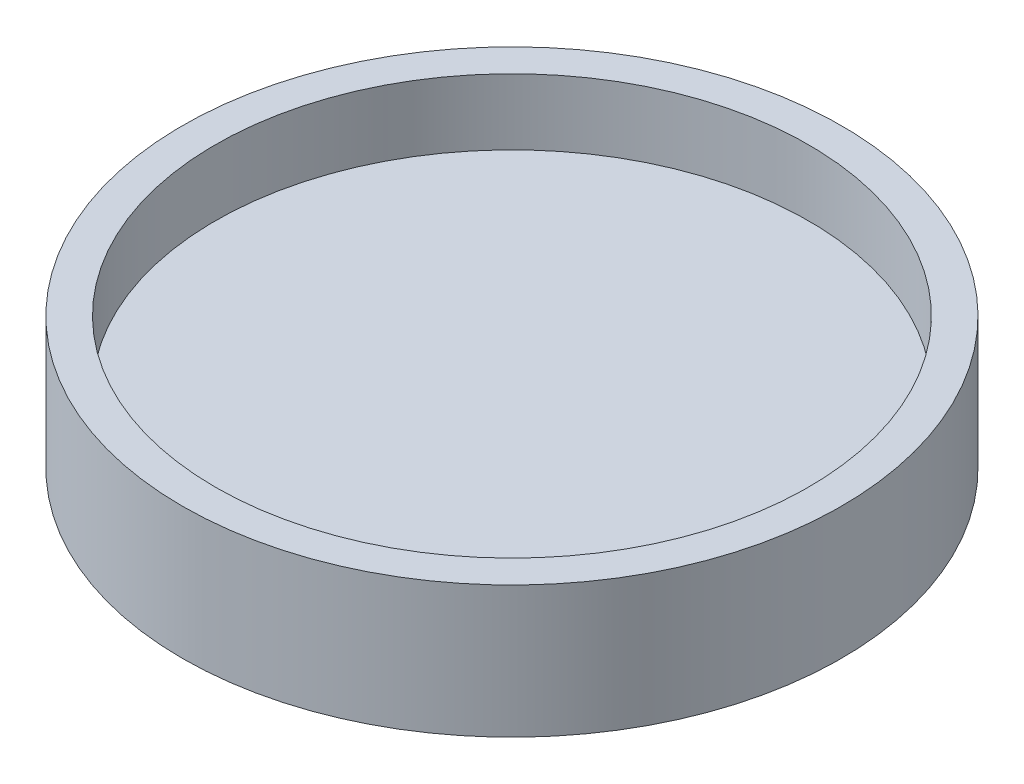
SolidWorks part; units mm, degrees
ref_plane "前基準面" through (0, 0, 0) normal (0, 0, 1) x (1, 0, 0)
ref_plane "上基準面" through (0, 0, 0) normal (0, 1, 0) x (1, 0, 0)
ref_plane "右基準面" through (0, 0, 0) normal (1, 0, 0) x (0, 0, -1)
sketch "草圖1" plane through (0, 0, 0) normal (0, 1, 0) x (1, 0, 0)
  circle A0 centre (0, 0) radius 25
  dimension "D1" = 50
extrude "填料-伸長1" add sketch "草圖1" along normal blind 10
sketch "草圖3" plane through (0, 10, 0) normal (0, 1, 0) x (1, 0, 0)
  circle A0 centre (0, 0) radius 22.5
  dimension "D1" = 45
extrude "除料-伸長1" cut sketch "草圖3" against normal blind 5
